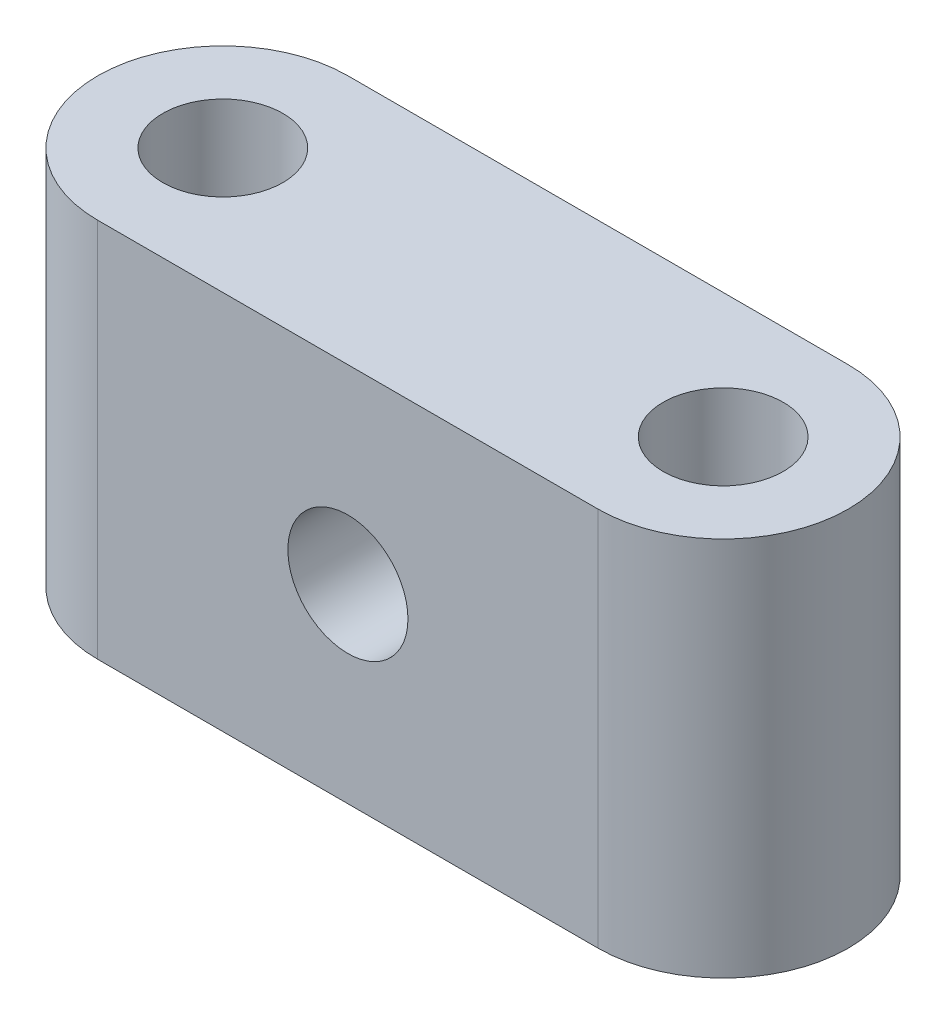
SolidWorks part; units mm, degrees
ref_plane "Płaszczyzna przednia" through (0, 0, 0) normal (0, 0, 1) x (1, 0, 0)
ref_plane "Płaszczyzna górna" through (0, 0, 0) normal (0, 1, 0) x (1, 0, 0)
ref_plane "Płaszczyzna prawa" through (0, 0, 0) normal (1, 0, 0) x (0, 0, -1)
sketch "Szkic1" plane through (0, 0, 0) normal (0, 1, 0) x (1, 0, 0)
  line L0 (0, 0) -> (50, 0) construction
  line L1 (0, 12.5) -> (50, 12.5)
  line L2 (0, -12.5) -> (50, -12.5)
  arc A0 (0, 12.5) -> (0, -12.5) centre (0, 0) ccw
  arc A1 (50, -12.5) -> (50, 12.5) centre (50, 0) ccw
  circle A2 centre (0, 0) radius 6
  circle A3 centre (50, 0) radius 6
  point P3 (25, 0)
  dimension "D2" = 12.5
  dimension "D3" = 12
  dimension "D1" = 50
extrude "Dodanie-wyciągnięcie1" add sketch "Szkic1" along normal blind 38
sketch "Szkic2" plane through (0, 0, 12.5) normal (0, 0, 1) x (1, 0, 0)
  line L0 (25, 38) -> (25, 0) construction
  line L1 (0, 38) -> (50, 38) construction
  line L2 (0, 0) -> (50, 0) construction
  circle A0 centre (25, 19) radius 6
  dimension "D1" = 12
extrude "Wytnij-wyciągnięcie1" cut sketch "Szkic2" against normal blind 12.5
